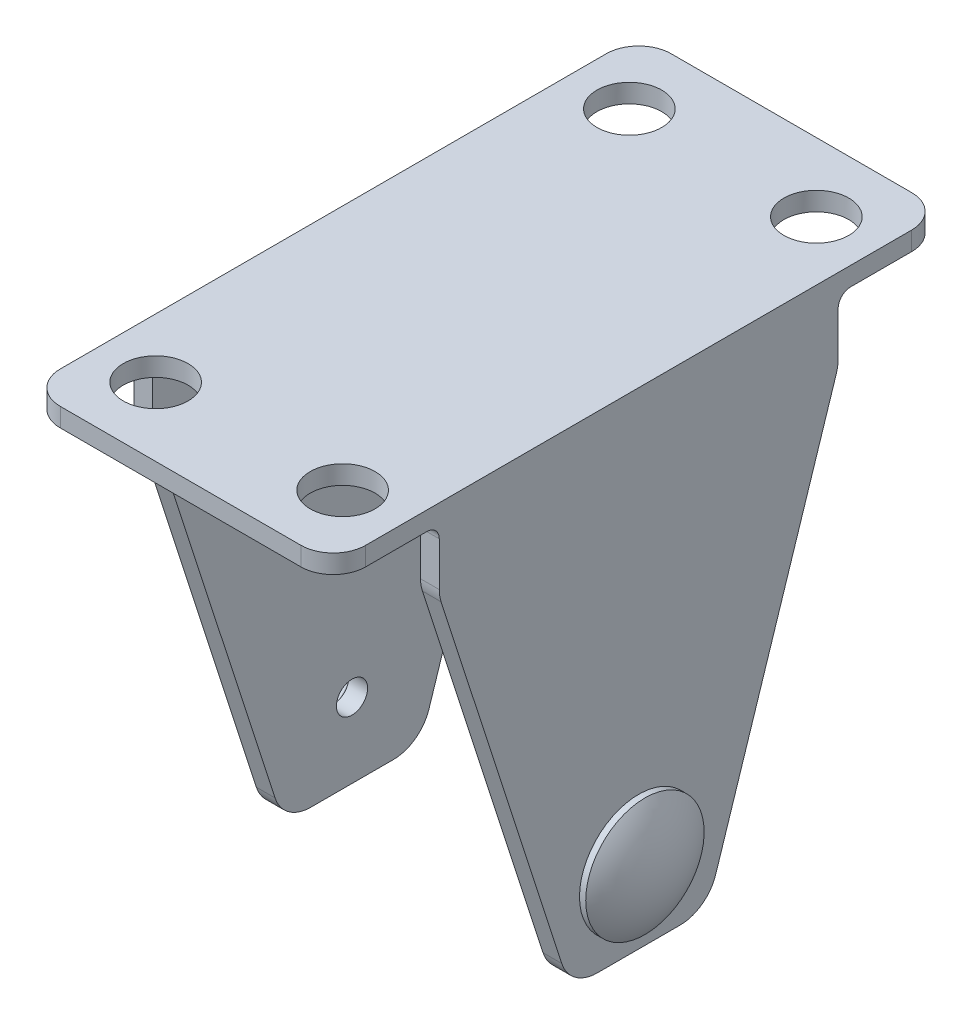
SolidWorks part; units mm, degrees
ref_plane "前视基准面" through (0, 0, 0) normal (0, 0, 1) x (1, 0, 0)
ref_plane "上视基准面" through (0, 0, 0) normal (0, 1, 0) x (1, 0, 0)
ref_plane "右视基准面" through (0, 0, 0) normal (1, 0, 0) x (0, 0, -1)
sketch "草图1" plane through (0, 0, 0) normal (0, 1, 0) x (1, 0, 0)
  line L0 (43.6464, 39.8273) -> (43.6464, 88.8273)
  line L1 (43.6464, 88.8273) -> (68.1464, 88.8273)
  line L2 (68.1464, 88.8273) -> (68.1464, 39.8273)
  line L3 (68.1464, 39.8273) -> (43.6464, 39.8273)
extrude "凸台-拉伸1" add sketch "草图1" along normal blind 1.5
sketch "草图2" plane through (68.1464, 0, 0) normal (1, 0, 0) x (0, 0, -1)
  line L1 (39.8273, 1.5) -> (88.8273, 1.5) construction
  line L3 (69.8273, -37.5) -> (58.8273, -37.5)
  line L4 (64.3273, 1.5) -> (48.3273, 1.5)
  line L5 (48.3273, 1.5) -> (48.3273, -5)
  line L6 (48.3273, -5) -> (58.8273, -37.5)
  line L7 (80.3273, -5) -> (69.8273, -37.5)
  line L8 (80.3273, 1.5) -> (80.3273, -5)
  line L9 (64.3273, 1.5) -> (80.3273, 1.5)
extrude "凸台-拉伸2" add sketch "草图2" against normal blind 1.5
sketch "草图4" plane through (43.6464, 0, 0) normal (-1, 0, 0) x (0, 0, 1)
  line L6 (-48.3273, -5) -> (-48.3273, 0)
  line L7 (-48.3273, 0) -> (-80.3273, 0)
  line L8 (-80.3273, 0) -> (-80.3273, -5)
  line L9 (-80.3273, -5) -> (-69.8273, -37.5)
  line L10 (-69.8273, -37.5) -> (-58.8273, -37.5)
  line L11 (-58.8273, -37.5) -> (-48.3273, -5)
  line L12 (-48.3273, -5) -> (-48.3273, 0)
  line L13 (-48.3273, 0) -> (-80.3273, 0)
  line L14 (-80.3273, 0) -> (-80.3273, -5)
  line L15 (-80.3273, -5) -> (-69.8273, -37.5)
  line L16 (-69.8273, -37.5) -> (-58.8273, -37.5)
  line L17 (-58.8273, -37.5) -> (-48.3273, -5)
  dimension "D1" = 0
extrude "凸台-拉伸3" add sketch "草图4" against normal blind 1.5
sketch "草图5" plane through (0, 1.5, 0) normal (0, 1, 0) x (1, 0, 0)
  circle A0 centre (48.3964, 83.3273) radius 2.6
  circle A1 centre (63.3964, 83.3273) radius 2.6
  circle A2 centre (63.3964, 45.3273) radius 2.6
  circle A3 centre (48.3964, 45.3273) radius 2.6
extrude "切除-拉伸1" cut sketch "草图5" against normal through all
fillet "圆角1" radius 2.6 4 edges at (68.1464, 0.75, -88.8273) (43.6464, 0.75, -88.8273) (68.1464, 0.75, -39.8273) (43.6464, 0.75, -39.8273)
sketch "草图6" plane through (43.6464, 0, 0) normal (-1, 0, 0) x (0, 0, 1)
  circle A0 centre (-64.3273, -31.5) radius 1.25
extrude "切除-拉伸2" cut sketch "草图6" against normal through all
fillet "圆角2" radius 3 8 edges at (44.3964, -5, -48.3273) (67.3964, -5, -48.3273) (67.3964, -5, -80.3273) (44.3964, -5, -80.3273) (67.3964, -37.5, -69.8273) (67.3964, -37.5, -58.8273) (44.3964, -37.5, -58.8273) (44.3964, -37.5, -69.8273)
fillet "圆角3" radius 1 4 edges at (67.3964, 0, -48.3273) (44.3964, 0, -48.3273) (67.3964, 0, -80.3273) (44.3964, 0, -80.3273)
ref_axis "基准轴1" through (68.1464, -31.5, -64.3273) along (-1, 0, 0)
ref_plane "基准面1" through (0, 0, -64.3273) normal (0, 0, 1) x (-1, 0, 0)
sketch "草图9" plane through (0, 0, -64.3273) normal (0, 0, 1) x (-1, 0, 0)
  line L0 (-68.1464, 32.75) -> (-68.1464, 30.25) construction
  line L2 (-68.1464, 31.5) -> (-68.1464, 26.75)
  line L3 (-68.1464, 31.5) -> (-70.1464, 31.5)
  line L5 (-68.1464, 26.75) -> (-68.6464, 26.75)
  arc A0 (-70.1464, 31.5) -> (-68.6464, 26.75) centre (-61.8756, 31.5) ccw
revolve "旋转1" add sketch "草图9" angle 360 about L3
sketch "草图10" plane through (0, 0, -64.3273) normal (0, 0, 1) x (-1, 0, 0)
  line L3 (-42.1464, 28.5) -> (-42.1464, 28.25)
  line L6 (-43.6464, 28.25) -> (-43.6464, 29.25)
  line L8 (-42.8964, 29.25) -> (-43.6464, 29.25)
  arc A0 (-43.6464, 28.25) -> (-42.1464, 28.25) centre (-42.8964, 28.25) ccw
  arc A1 (-42.8964, 29.25) -> (-42.1464, 28.5) centre (-42.8964, 28.5) cw
revolve "旋转2" add sketch "草图10" angle 360 about axis through (68.1464, -31.5, -64.3273) along (-1, 0, 0)
